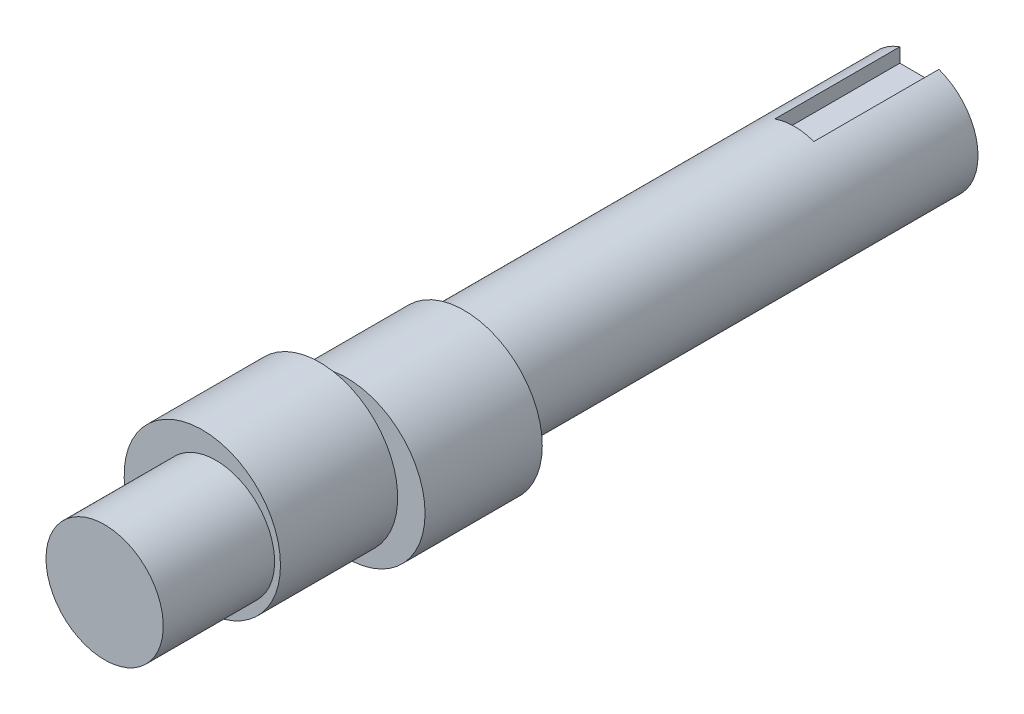
SolidWorks part; units mm, degrees
ref_plane "Plan de face" through (0, 0, 0) normal (0, 0, 1) x (1, 0, 0)
ref_plane "Plan de dessus" through (0, 0, 0) normal (0, 1, 0) x (1, 0, 0)
ref_plane "Plan de droite" through (0, 0, 0) normal (1, 0, 0) x (0, 0, -1)
sketch "Esquisse2" plane through (0, 0, 0) normal (0, 0, 1) x (1, 0, 0)
  circle A0 centre (0, 0) radius 7.5
  dimension "D1" = 15
extrude "Boss.-Extru.1" add sketch "Esquisse2" along normal blind 60
sketch "Esquisse3" plane through (0, 0, 60) normal (0, 0, 1) x (1, 0, 0)
  circle A0 centre (1.75, 0) radius 10
  dimension "D1" = 20
  dimension "D2" = 1.75
extrude "Boss.-Extru.2" add sketch "Esquisse3" along normal blind 15
sketch "Esquisse4" plane through (0, 0, 75) normal (0, 0, 1) x (1, 0, 0)
  circle A0 centre (-1.75, 0) radius 10
  dimension "D1" = 20
  dimension "D2" = 1.75
extrude "Boss.-Extru.3" add sketch "Esquisse4" along normal blind 15
sketch "Esquisse5" plane through (0, 0, 90) normal (0, 0, 1) x (1, 0, 0)
  circle A0 centre (0, 0) radius 7.5
  dimension "D1" = 15
extrude "Boss.-Extru.4" add sketch "Esquisse5" along normal blind 14.25
sketch "Esquisse6" plane through (0, 0, 0) normal (0, 0, -1) x (-1, 0, 0)
  line L0 (-2.5, 7.0711) -> (-2.5, 5.25)
  line L1 (-2.5, 5.25) -> (2.5, 5.25)
  line L2 (2.5, 5.25) -> (2.5, 7.0711)
  circle A0 centre (0, 0) radius 7.5 construction
  arc A3 (2.5, 7.0711) -> (-2.5, 7.0711) centre (0, 0) ccw
  dimension "D1" = 5
  dimension "D2" = 2.5
  dimension "D3" = 5.25
extrude "Enlèv. mat.-Extru.1" cut sketch "Esquisse6" against normal blind 16
